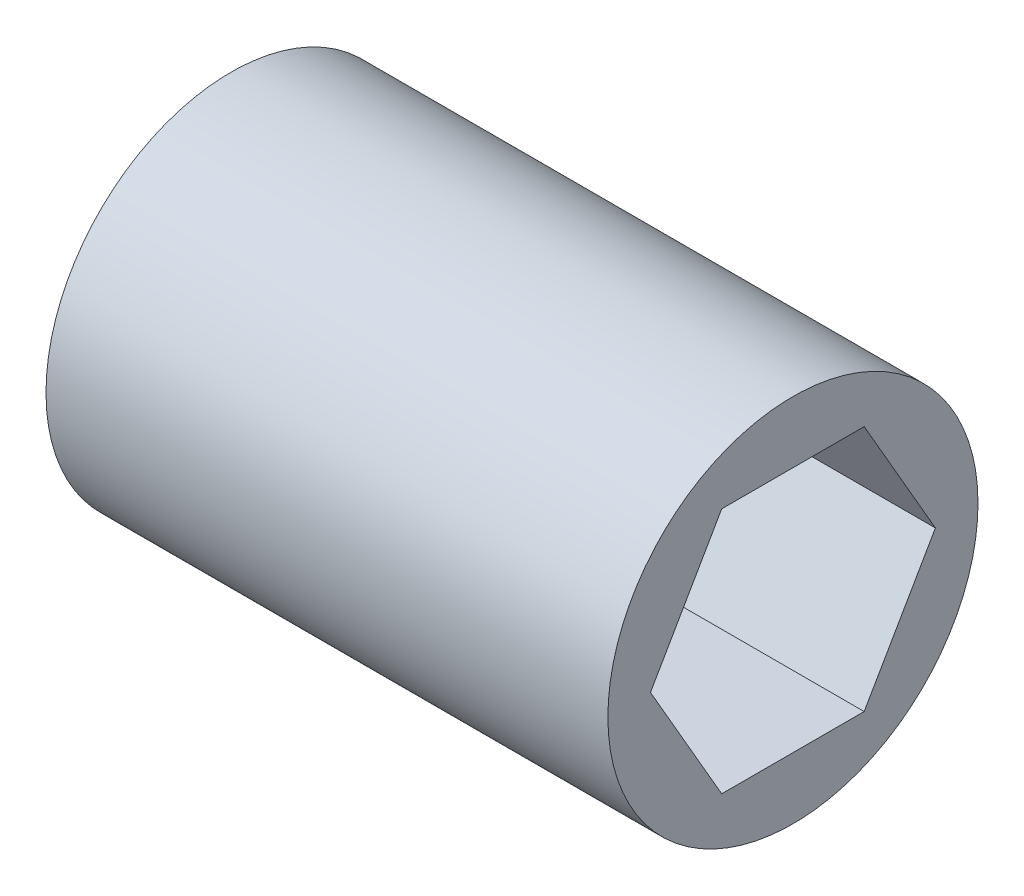
SolidWorks part; units mm, degrees
material "POM Acetal Copolymer"
ref_plane "Front Plane" through (0, 0, 0) normal (0, 0, 1) x (1, 0, 0)
ref_plane "Top Plane" through (0, 0, 0) normal (0, 1, 0) x (1, 0, 0)
ref_plane "Right Plane" through (0, 0, 0) normal (1, 0, 0) x (0, 0, -1)
sketch "Sketch1" plane through (0, 0, 0) normal (1, 0, 0) x (0, 0, -1)
  line L1 (7.3323, 0) -> (3.6662, 6.35)
  line L2 (3.6662, 6.35) -> (-3.6662, 6.35)
  line L3 (-3.6662, 6.35) -> (-7.3323, 0)
  line L4 (-7.3323, 0) -> (-3.6662, -6.35)
  line L5 (-3.6662, -6.35) -> (3.6662, -6.35)
  line L6 (3.6662, -6.35) -> (7.3323, 0)
  circle A0 centre (0, 0) radius 6.35 construction
  circle A1 centre (0, 0) radius 9.525
  dimension "D1" = 12.7
  dimension "D2" = 3.175
extrude "Boss-Extrude1" add sketch "Sketch1" along normal mid plane 28.92
